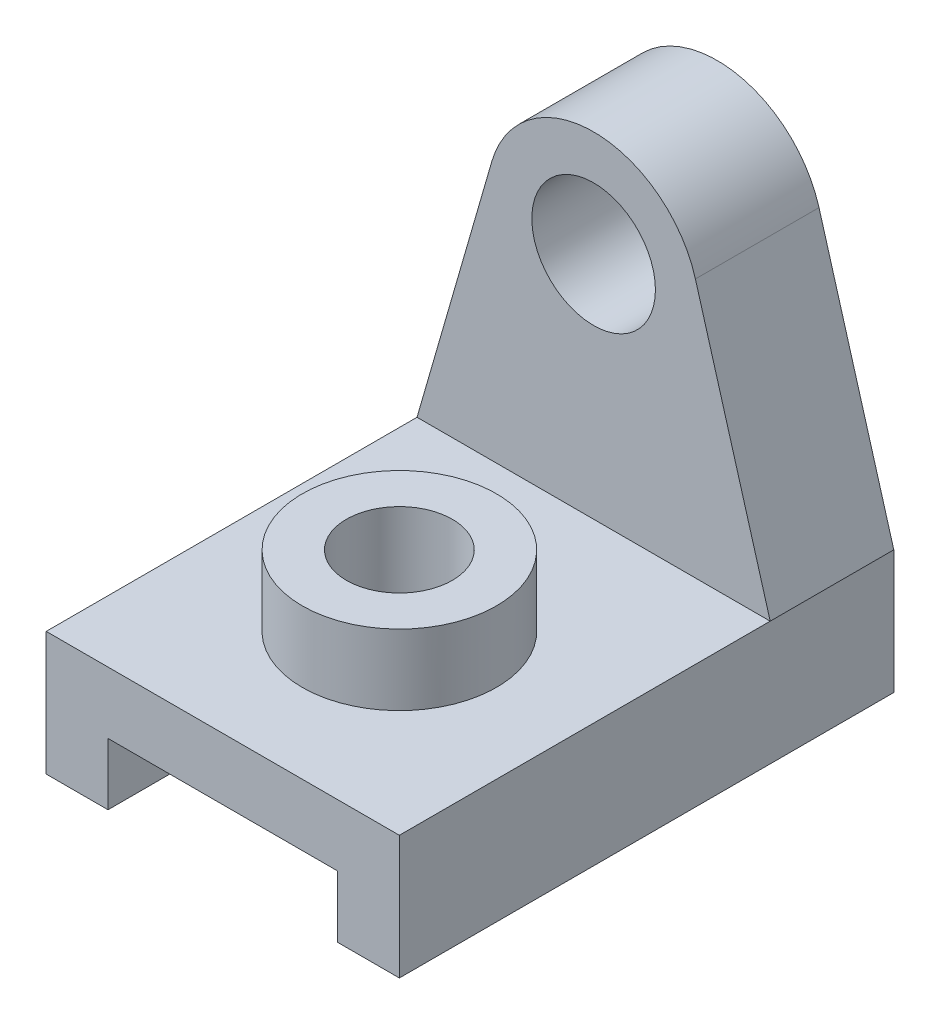
SolidWorks part; units mm, degrees
ref_plane "Front Plane" through (0, 0, 0) normal (0, 0, 1) x (1, 0, 0)
ref_plane "Top Plane" through (0, 0, 0) normal (0, 1, 0) x (1, 0, 0)
ref_plane "Right Plane" through (0, 0, 0) normal (1, 0, 0) x (0, 0, -1)
sketch "Sketch1" plane through (0, 0, 0) normal (0, 1, 0) x (1, 0, 0)
  line L0 (-20, 0) -> (20, 0)
  line L1 (20, 0) -> (20, -56)
  line L2 (20, -56) -> (-20, -56)
  line L3 (0, 0) -> (0, 26.4922)
  line L4 (-20, 0) -> (-20, -56)
  point P7 (0, -56)
extrude "Boss-Extrude1" add sketch "Sketch1" along normal blind 14 contours L4 L2 L1 L0
sketch "Sketch5" plane through (0, 0, 0) normal (0, 0, 1) x (1, 0, 0)
  line L0 (13, 0) -> (13, 7)
  line L5 (13, 0) -> (-13, 0)
  line L6 (0, 0) -> (0, 7)
  line L7 (13, 7) -> (-13, 7)
  line L8 (-13, 0) -> (-13, 7)
extrude "Cut-Extrude1" cut sketch "Sketch5" along normal blind 68 contours L0 L7 L6 L5 | L8 L5 L6 L7
sketch "Sketch7" plane through (0, 0, 0) normal (0, 0, 1) x (1, 0, 0)
  line L0 (20, 14) -> (-20, 14)
  line L2 (0, -7.7) -> (0, 7.7) construction
  line L3 (20, 14) -> (11.5288, 43.3298)
  line L4 (-20, 14) -> (-11.5288, 43.3298)
  circle A0 centre (0, 40) radius 7
  arc A1 (11.5288, 43.3298) -> (-11.5288, 43.3298) centre (0, 40) ccw
extrude "Boss-Extrude2" add sketch "Sketch7" along normal blind 14
sketch "Sketch8" plane through (0, 14, 0) normal (0, 1, 0) x (1, 0, 0)
  line L0 (0, -47) -> (0, -36)
  line L2 (0, -28.6) -> (0, 28.6) construction
  circle A0 centre (0, -36) radius 11
extrude "Boss-Extrude3" add sketch "Sketch8" along normal blind 8 and the other way blind 1
sketch "Sketch9" plane through (0, 22, 0) normal (0, 1, 0) x (1, 0, 0)
  line L2 (0, -28.6) -> (0, 28.6) construction
  circle A0 centre (0, -36) radius 6
extrude "Cut-Extrude2" cut sketch "Sketch9" against normal blind 44
